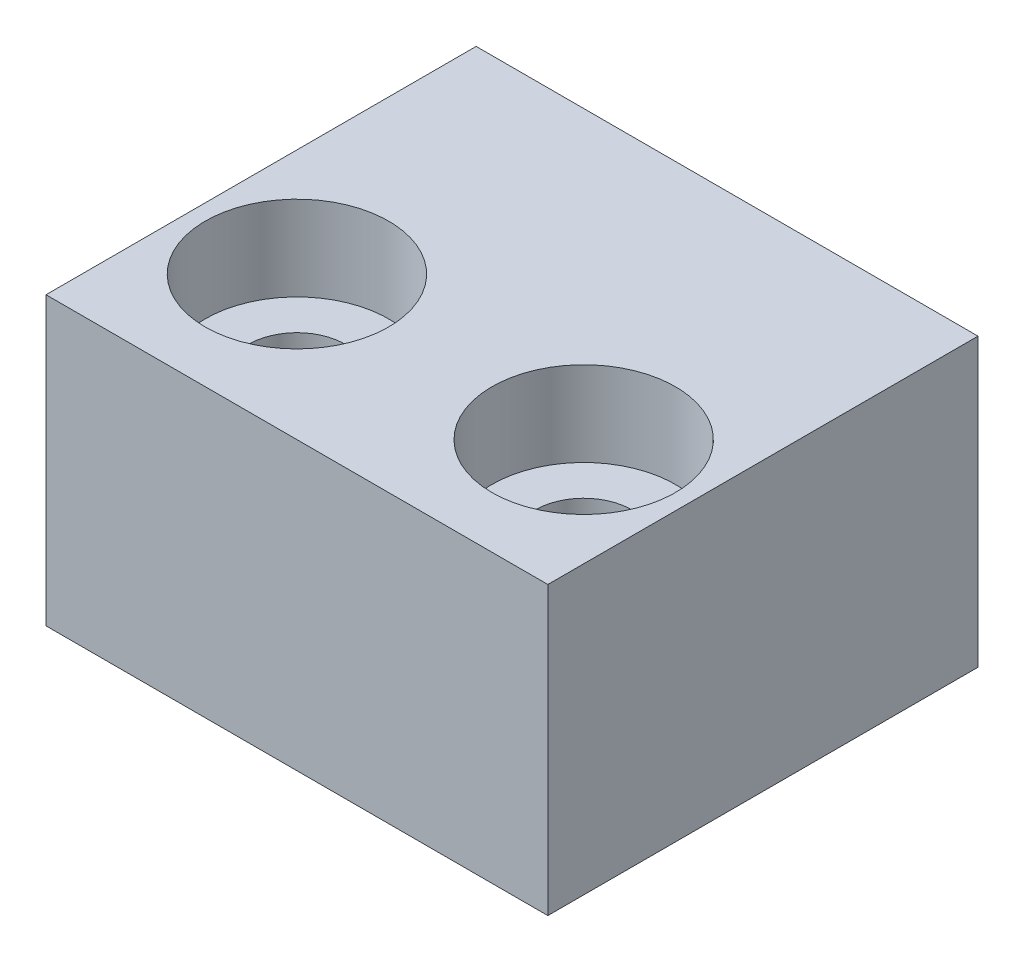
SolidWorks part; units mm, degrees
ref_plane "Front Plane" through (0, 0, 0) normal (0, 0, 1) x (1, 0, 0)
ref_plane "Top Plane" through (0, 0, 0) normal (0, 1, 0) x (1, 0, 0)
ref_plane "Right Plane" through (0, 0, 0) normal (1, 0, 0) x (0, 0, -1)
sketch "Sketch1" plane through (0, 0, 0) normal (0, 1, 0) x (1, 0, 0)
  line L0 (3.81, 5.08) -> (13.97, 5.08) construction
  line L1 (0, 0) -> (17.78, 0)
  line L2 (0, 0) -> (0, 15.24)
  line L3 (0, 15.24) -> (17.78, 15.24)
  line L4 (17.78, 0) -> (17.78, 15.24)
  line L5 (8.89, 15.24) -> (8.89, 0) construction
  dimension "D2" = 5.08
  dimension "D1" = 15.24
  dimension "D3" = 17.78
  dimension "D4" = 10.16
extrude "Boss-Extrude1" add sketch "Sketch1" along normal blind 10.16
sketch "Sketch6" plane through (0, 10.16, 0) normal (0, 1, 0) x (1, 0, 0)
  point P0 (3.81, 5.08)
  point P3 (13.97, 5.08)
hole_wizard "CBORE for M3 SHCS1" positions "Sketch6" profile "Sketch5" counterbore size "M3" standard "ANSI Metric" end condition through all
sketch "Sketch5" plane through (3.81, 10.16, -5.08) normal (1, 0, 0) x (0, 0, 1)
  line L0 (0, 0) -> (0, 10.16)
  line L1 (0, 10.16) -> (1.7, 10.16)
  line L3 (1.7, 10.16) -> (1.7, 3)
  line L4 (1.7, 3) -> (3.25, 3)
  line L5 (3.25, 3) -> (3.25, 0)
  line L7 (3.25, 0) -> (0, 0)
  line L11 (0, -6.35) -> (0, 107.95) construction
  dimension "Thru Hole Dia." = 3.4
  dimension "Thru Hole Depth" = 10.16
  dimension "C'Bore Dia." = 6.5
  dimension "C'Bore Depth" = 3
